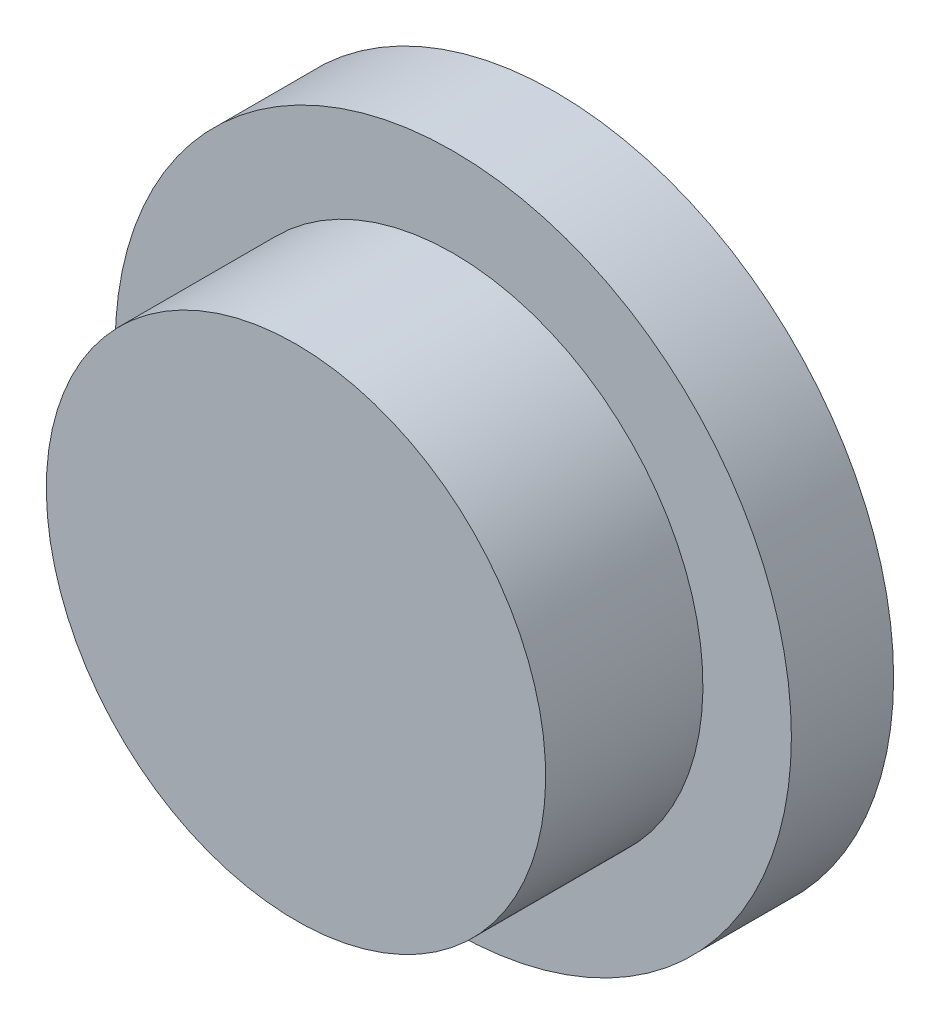
SolidWorks part; units mm, degrees
ref_plane "Спереди" through (0, 0, 0) normal (0, 0, 1) x (1, 0, 0)
ref_plane "Сверху" through (0, 0, 0) normal (0, 1, 0) x (1, 0, 0)
ref_plane "Справа" through (0, 0, 0) normal (1, 0, 0) x (0, 0, -1)
sketch "Эскиз1" plane through (0, 0, 0) normal (1, 0, 0) x (0, 0, -1)
  line L0 (6, 0) -> (0, 0)
  line L1 (0, 0) -> (0, 31.75)
  line L2 (0, 31.75) -> (20, 31.75)
  line L3 (20, 31.75) -> (20, 43)
  line L4 (20, 43) -> (33, 43)
  line L5 (33, 43) -> (33, 40)
  line L6 (33, 40) -> (27, 40)
  line L7 (27, 40) -> (27, 37)
  line L8 (27, 37) -> (30, 37)
  line L9 (30, 37) -> (30, 27)
  line L10 (30, 27) -> (3, 19)
  line L11 (3, 19) -> (3, 14)
  line L12 (3, 14) -> (6, 14)
  line L13 (6, 14) -> (6, 0)
  dimension "D1" = 31.75
  dimension "D2" = 14
  dimension "D3" = 19
  dimension "D4" = 3
  dimension "D5" = 43
  dimension "D6" = 13
  dimension "D7" = 33
  dimension "D8" = 3
  dimension "D9" = 3
  dimension "D10" = 3
  dimension "D11" = 3
  dimension "D12" = 27
  dimension "D13" = 27
  dimension "D14" = 3
revolve "Повернуть1" add sketch "Эскиз1" angle 360 about L0
